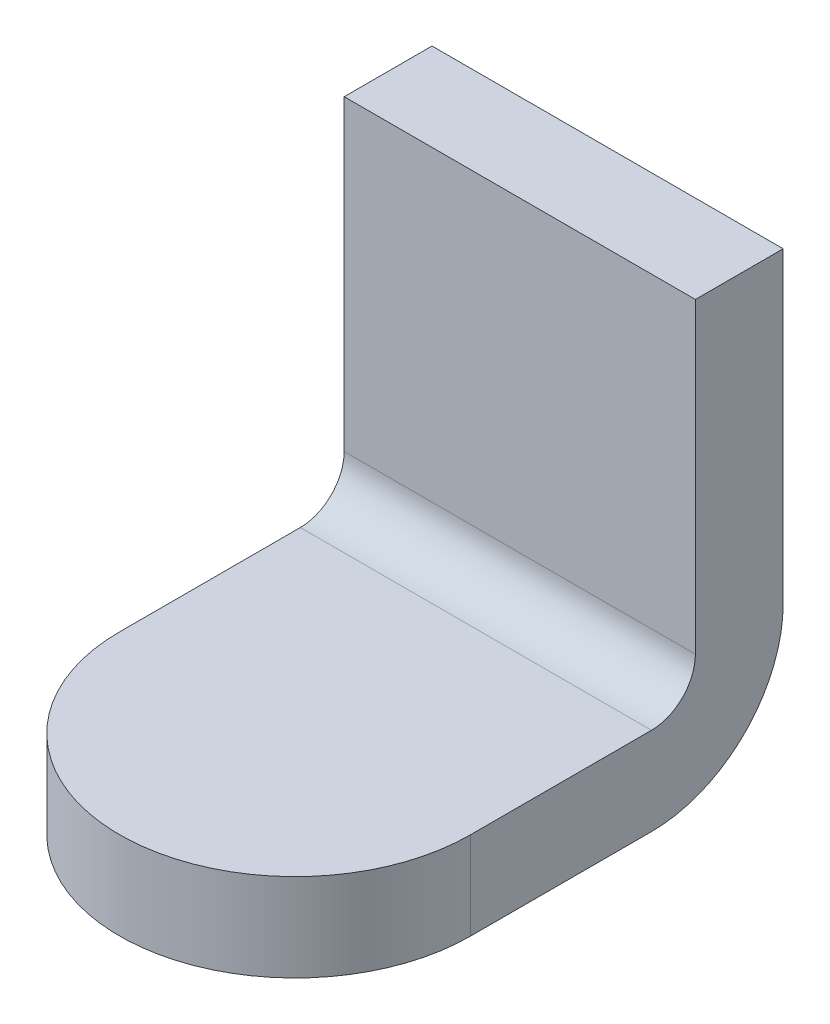
SolidWorks part; units mm, degrees
ref_plane "前视基准面" through (0, 0, 0) normal (0, 0, 1) x (1, 0, 0)
ref_plane "上视基准面" through (0, 0, 0) normal (0, 1, 0) x (1, 0, 0)
ref_plane "右视基准面" through (0, 0, 0) normal (1, 0, 0) x (0, 0, -1)
sketch "草图3" plane through (0, 0, 0) normal (0, 1, 0) x (1, 0, 0)
  line L0 (-40, 0) -> (-40, 71.1894)
  line L1 (-40, 71.1894) -> (40, 71.1894)
  line L2 (40, 71.1894) -> (40, 0)
  circle A0 centre (0, 0) radius 40
  dimension "D1" = 80
extrude "凸台-拉伸1" add sketch "草图3" along normal blind 20 contours A0 L2 L1 L0 | A0
sketch "草图4" plane through (0, 20, 0) normal (0, 1, 0) x (1, 0, 0)
  line L0 (40, 71.1894) -> (40, 0) construction
  line L1 (-40, 71.1894) -> (40, 71.1894)
  line L2 (-40, 71.1894) -> (-40, 51.1894)
  line L3 (-40, 51.1894) -> (40, 51.1894)
  line L4 (40, 71.1894) -> (40, 51.1894)
  dimension "D1" = 20
extrude "凸台-拉伸2" add sketch "草图4" along normal blind 80
fillet "圆角2" radius 10 1 edges at (0, 20, -51.1894)
fillet "圆角3" radius 30 1 edges at (0, 0, -71.1894)
